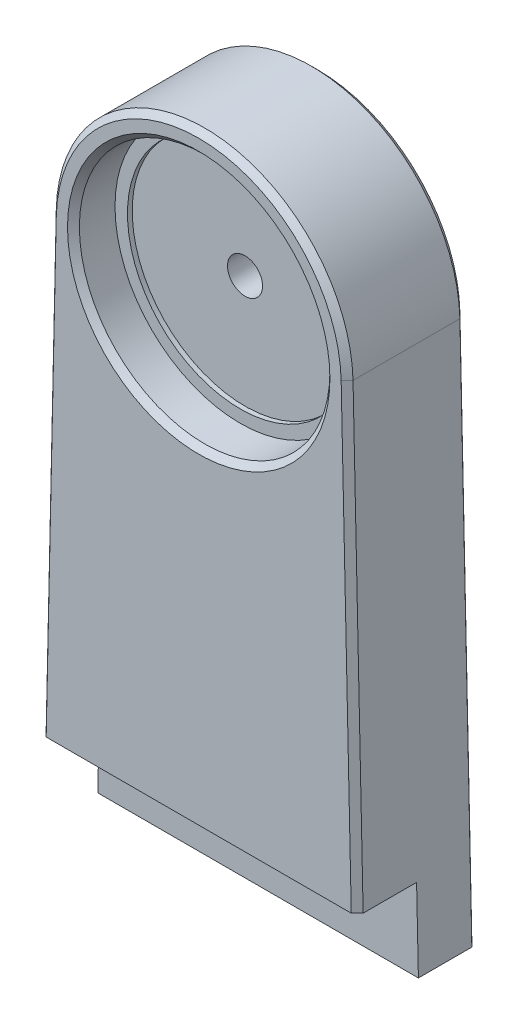
SolidWorks part; units mm, degrees
ref_plane "前视基准面" through (0, 0, 0) normal (0, 0, 1) x (1, 0, 0)
ref_plane "上视基准面" through (0, 0, 0) normal (0, 1, 0) x (1, 0, 0)
ref_plane "右视基准面" through (0, 0, 0) normal (1, 0, 0) x (0, 0, -1)
sketch "草图2" plane through (0, 0, 0) normal (0, 0, 1) x (1, 0, 0)
  line L0 (-24.9912, 0.6635) -> (-27, -90)
  line L1 (24.9912, 0.6635) -> (27, -90)
  line L2 (0, -90) -> (-27, -90)
  line L5 (0, -90) -> (27, -90)
  arc A0 (24.9912, 0.6635) -> (-24.9912, 0.6635) centre (0, 0) ccw
  circle A4 centre (0, 0) radius 2.95
  circle A5 centre (-15, -83) radius 1.55
  circle A6 centre (0, -83) radius 1.55
  circle A7 centre (15, -83) radius 1.55
extrude "凸台-拉伸1" add sketch "草图2" along normal blind 20
sketch "草图3" plane through (0, 0, 20) normal (0, 0, 1) x (1, 0, 0)
  line L0 (-27, -90) -> (-27, -76.2)
  line L1 (27, -90) -> (27, -76.2)
  line L3 (-27, -76.2) -> (27, -76.2)
  line L4 (27, -90) -> (-27, -90)
extrude "切除-拉伸1" cut sketch "草图3" against normal blind 10
sketch "草图4" plane through (0, 0, 20) normal (0, 0, 1) x (1, 0, 0)
  circle A0 centre (0, 0) radius 21.1
extrude "切除-拉伸2" cut sketch "草图4" against normal blind 7
sketch "草图5" plane through (0, 0, 13) normal (0, 0, 1) x (1, 0, 0)
  circle A0 centre (0, 0) radius 19
extrude "切除-拉伸3" cut sketch "草图5" against normal blind 0.8
chamfer "倒角1" distance 1 angle 45 7 edges at (-25.9956, -44.6683, 0) (0, 25, 0) (25.9956, -44.6683, 0) (21.1, 0, 20) (25.8427, -37.7683, 20) (-25.8427, -37.7683, 20) (0, 25, 20)
sketch "草图6" plane through (0, 0, 0) normal (0, 0, -1) x (-1, 0, 0)
  circle A0 centre (-15, -83) radius 3
  circle A1 centre (0, -83) radius 3
  circle A2 centre (15, -83) radius 3
extrude "切除-拉伸4" cut sketch "草图6" against normal blind 3
